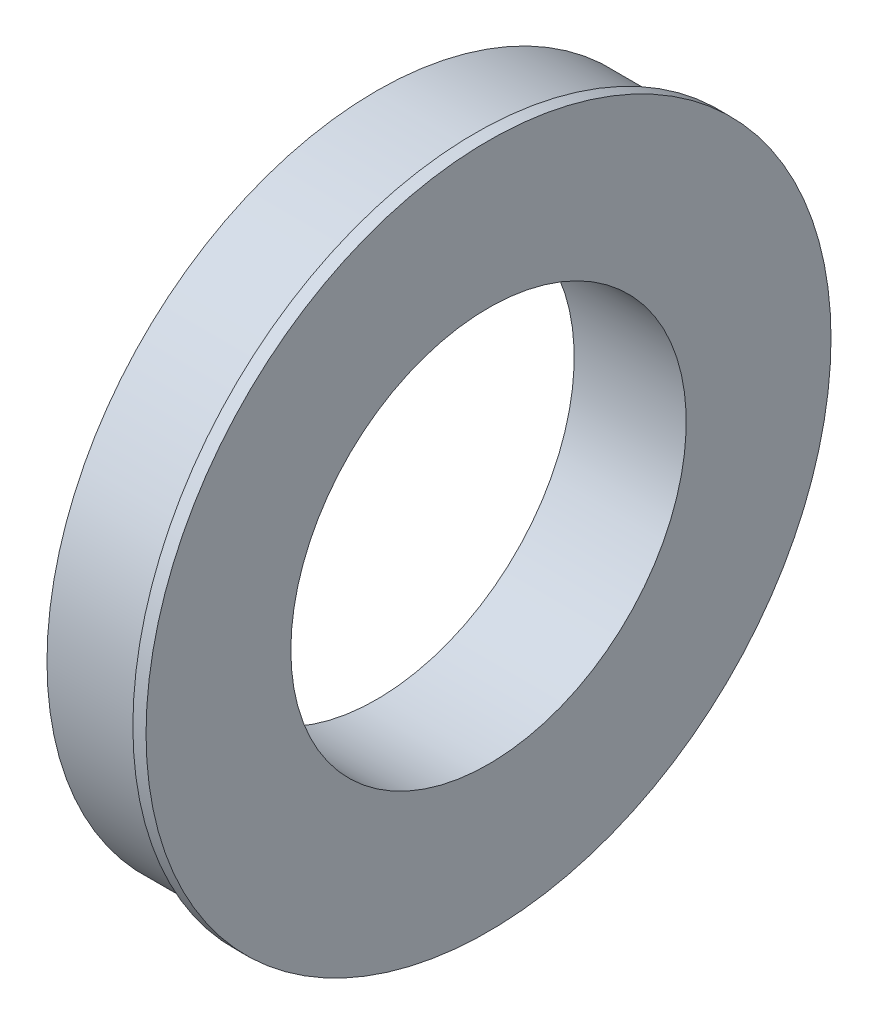
SolidWorks part; units mm, degrees
ref_plane "Front Plane" through (0, 0, 0) normal (0, 0, 1) x (1, 0, 0)
ref_plane "Top Plane" through (0, 0, 0) normal (0, 1, 0) x (1, 0, 0)
ref_plane "Right Plane" through (0, 0, 0) normal (1, 0, 0) x (0, 0, -1)
sketch "Sketch1" plane through (0, 0, 0) normal (1, 0, 0) x (0, 0, -1)
  circle A0 centre (0, 0) radius 63.5
  circle A1 centre (0, 0) radius 38.1
  dimension "D1" = 127
  dimension "D2" = 76.2
extrude "Boss-Extrude1" add sketch "Sketch1" along normal blind 19.05
sketch "Sketch3" plane through (19.05, 0, 0) normal (1, 0, 0) x (0, 0, -1)
  circle A0 centre (0, 0) radius 38.1 construction
  circle A1 centre (0, 0) radius 38.1
  circle A2 centre (0, 0) radius 66
  dimension "D1" = 132
extrude "Boss-Extrude2" add sketch "Sketch3" along normal blind 2.54
